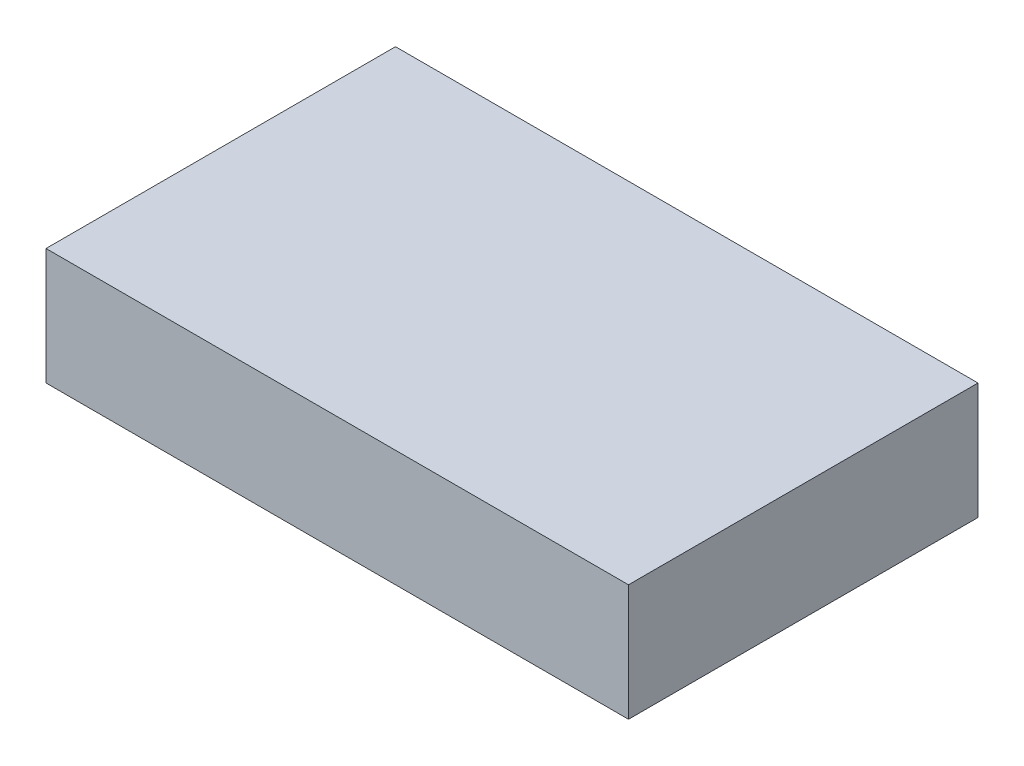
SolidWorks part; units mm, degrees
ref_plane "Front Plane" through (0, 0, 0) normal (0, 0, 1) x (1, 0, 0)
ref_plane "Top Plane" through (0, 0, 0) normal (0, 1, 0) x (1, 0, 0)
ref_plane "Right Plane" through (0, 0, 0) normal (1, 0, 0) x (0, 0, -1)
sketch "Sketch2" plane through (0, 0, 0) normal (0, 1, 0) x (1, 0, 0)
  line L1 (0, 0) -> (63.5, 0)
  line L2 (0, 0) -> (0, 38.1)
  line L3 (0, 38.1) -> (63.5, 38.1)
  line L4 (63.5, 0) -> (63.5, 38.1)
extrude "Boss-Extrude1" add sketch "Sketch2" along normal blind 12.7
